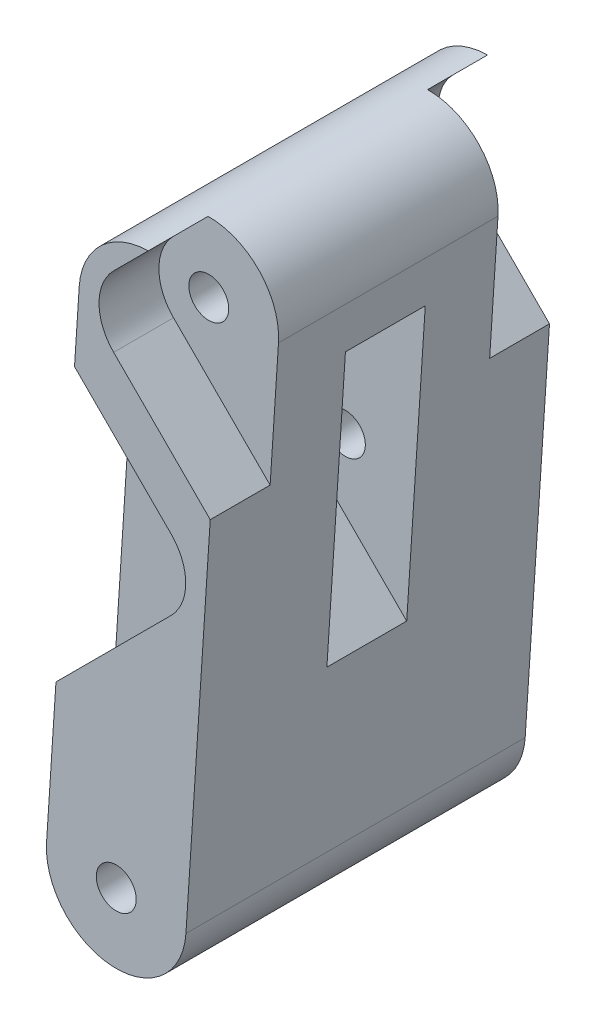
SolidWorks part; units mm, degrees
ref_plane "Спереди" through (0, 0, 0) normal (0, 0, 1) x (1, 0, 0)
ref_plane "Сверху" through (0, 0, 0) normal (0, 1, 0) x (1, 0, 0)
ref_plane "Справа" through (0, 0, 0) normal (1, 0, 0) x (0, 0, -1)
sketch "Sketch1" plane through (0, 0, 0) normal (0, 0, 1) x (1, 0, 0)
  line L0 (8.9343, 42.4002) -> (7.2968, 17.4539) construction
  line L5 (12.4268, 42.171) -> (10.7893, 17.2247)
  line L6 (5.4418, 42.6295) -> (3.8043, 17.6832)
  arc A2 (12.4268, 42.171) -> (5.4418, 42.6295) centre (8.9343, 42.4002) ccw
  arc A3 (3.8043, 17.6832) -> (10.7893, 17.2247) centre (7.2968, 17.4539) ccw
  circle A4 centre (7.2968, 17.4539) radius 1
  circle A5 centre (8.2793, 32.4217) radius 1
  circle A6 centre (8.9343, 42.4002) radius 1
  point P0 (8.1156, 29.9271)
  dimension "D3" = 2
  dimension "D2" = 7
  dimension "D10" = 10
  dimension "D11" = 15
extrude "Boss-Extrude1" add sketch "Sketch1" along normal blind 8.5
sketch "Sketch2" plane through (0, 0, 0) normal (0, 0, -1) x (-1, 0, 0)
  line L0 (-8.2793, 32.4217) -> (-8.2793, 34.9217) construction
  line L1 (-8.2793, 32.4217) -> (-5.7793, 34.9217) construction
  line L2 (-6.5115, 34.1895) -> (-13.367, 41.045)
  line L3 (-8.2793, 32.4217) -> (-5.7793, 32.4217) construction
  line L4 (-8.2793, 32.4217) -> (-5.7793, 29.9217)
  line L5 (-6.5115, 30.6539) -> (-11.353, 25.8125)
  line L6 (-10.7893, 17.2247) -> (-12.4268, 42.171) construction
  line L7 (-11.353, 25.8125) -> (-13.367, 41.045)
  line L8 (-7.2968, 17.4539) -> (-7.2968, 20.6352) construction
  line L9 (-7.2968, 17.4539) -> (-9.0646, 19.2217) construction
  line L10 (-9.0646, 19.2217) -> (-3.3092, 24.977)
  line L11 (-9.0646, 15.6861) -> (-3.3092, 9.9308)
  line L12 (-3.3092, 9.9308) -> (-3.3092, 24.977)
  arc A0 (-6.5115, 30.6539) -> (-6.5115, 34.1895) centre (-8.2793, 32.4217) ccw
  arc A1 (-9.0646, 19.2217) -> (-9.0646, 15.6861) centre (-7.2968, 17.4539) ccw
  dimension "D1" = 5
  dimension "D4" = 5
  dimension "D2" = 45
  dimension "D3" = 45
extrude "Cut-Extrude1" cut sketch "Sketch2" against normal blind 2
sketch "Sketch3" plane through (0, 0, 8.5) normal (0, 0, 1) x (1, 0, 0)
  line L0 (8.9343, 42.4002) -> (7.1665, 40.6325) construction
  line L1 (7.1665, 44.168) -> (14.1852, 51.1867)
  line L2 (7.1665, 40.6325) -> (14.7891, 33.0099)
  line L3 (14.1852, 51.1867) -> (14.7891, 33.0099)
  line L4 (8.2793, 32.4217) -> (10.0471, 34.1895) construction
  line L5 (8.2793, 32.4217) -> (10.0471, 30.6539) construction
  line L6 (10.0471, 34.1895) -> (4.0051, 40.2314)
  line L7 (4.0051, 40.2314) -> (3.2606, 23.8674)
  line L8 (3.2606, 23.8674) -> (10.0471, 30.6539)
  arc A0 (7.1665, 44.168) -> (7.1665, 40.6325) centre (8.9343, 42.4002) ccw
  arc A1 (10.0471, 30.6539) -> (10.0471, 34.1895) centre (8.2793, 32.4217) ccw
  dimension "D1" = 5
  dimension "D3" = 5
  dimension "D2" = 90
  dimension "D4" = 2.5
extrude "Cut-Extrude2" cut sketch "Sketch3" against normal blind 3
ref_plane "Plane1" through (0, 0, 0) normal (0, 0, -1) x (-1, 0, 0)
mirror "Mirror1" about plane through (0, 0, 0) normal (0, 0, -1) of "Boss-Extrude1", "Cut-Extrude1", "Cut-Extrude2"
ref_plane "Plane2" through (6.1247, -0.402, 0) normal (-0.9979, 0.0655, 0) x (0, 0, 1)
